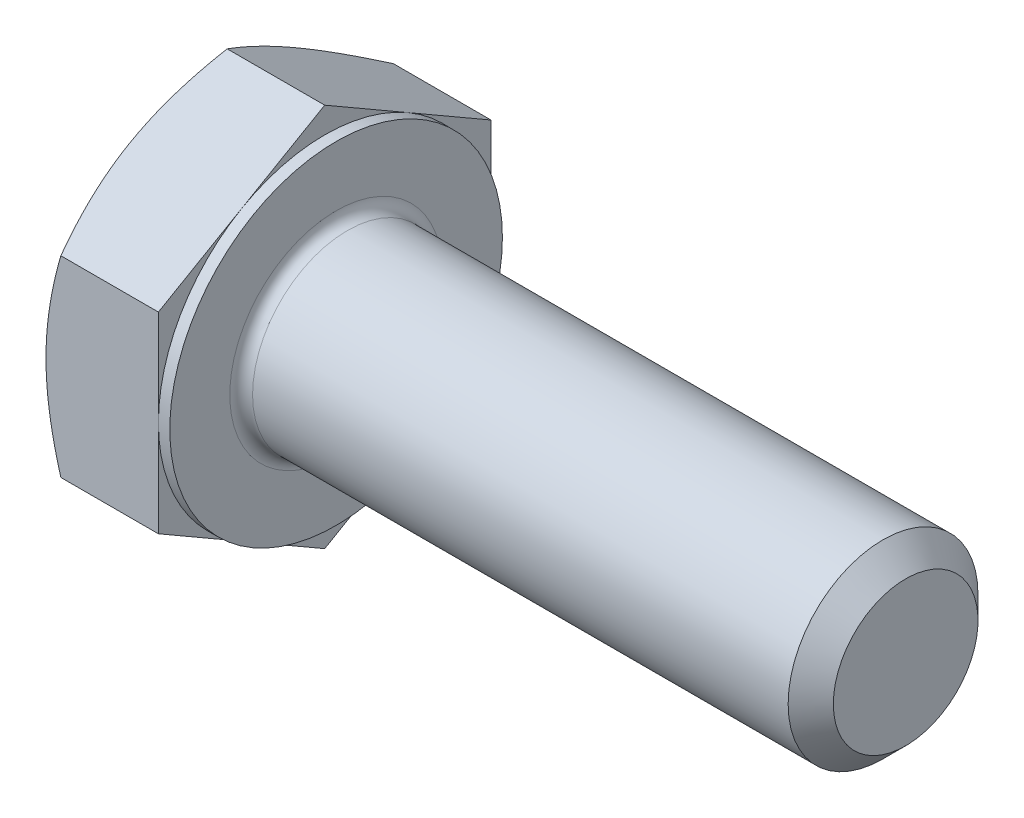
SolidWorks part; units mm, degrees
extrude "BaseHead" add sketch "Sketch1" along normal blind 4.1402
sketch "Sketch1" plane through (0, 0, 0) normal (1, 0, 0) x (0, 0, -1)
  line L0 (5.5626, 3.2116) -> (5.5626, -3.2116)
  line L1 (-5.5626, 3.2116) -> (-5.5626, -3.2116)
  line L2 (5.5626, -3.2116) -> (0, -6.4231)
  line L3 (0, -6.4231) -> (-5.5626, -3.2116)
  line L4 (5.5626, 3.2116) -> (0, 6.4231)
  line L5 (0, 6.4231) -> (-5.5626, 3.2116)
  dimension "Width_flats" = 11.1252
  dimension "D2" = 120
  dimension "D3" = 5.5626
  dimension "D4" = 5.5626
  dimension "D5" = 5.5626
revolve "HeadChamfer" cut sketch "Sketch3" angle 360 about L6
sketch "Sketch3" plane through (0, 0, 0) normal (0, 0, 1) x (1, 0, 0)
  line L0 (0, 5.5626) -> (4.163, 12.7731)
  line L1 (0, 6.4231) -> (0, 3.2116) construction
  line L2 (4.163, 12.7731) -> (4.163, 19.1231)
  line L3 (4.163, 19.1231) -> (-12.7, 19.1231)
  line L4 (-12.7, 19.1231) -> (-12.7, 5.5626)
  line L5 (-12.7, 5.5626) -> (0, 5.5626)
  line L6 (0, 0) -> (99.06, 0) construction
  line L7 (4.1402, 6.4231) -> (0, 6.4231) construction
  dimension "D1" = 5.5626
  dimension "D2" = 6.35
  dimension "D3" = 12.7
  dimension "D4" = 6.35
  dimension "Head_ch_ang" = 30
ref_plane "Plane1" through (0, 0, 0) normal (0, 0, 1) x (1, 0, 0)
ref_plane "Plane2" through (0, 0, 0) normal (0, 1, 0) x (1, 0, 0)
ref_plane "Plane3" through (0, 0, 0) normal (1, 0, 0) x (0, 0, -1)
sketch "BodySke" plane through (0, 0, 0) normal (0, 0, 1) x (1, 0, 0)
  line L0 (0, 3.2116) -> (0, -3.2116) construction
  line L1 (0, 0) -> (23.1902, 0)
  line L2 (0, 0) -> (0, 3.175)
  line L3 (0, 3.175) -> (22.4345, 3.175)
  line L4 (23.1902, 0) -> (23.1902, 2.4193)
  line L5 (4.1402, 6.4231) -> (4.1402, 3.2116) construction
  line L6 (23.1902, 2.4193) -> (22.4345, 3.175)
  line L7 (0, 0) -> (96.52, 0) construction
  line L8 (23.1902, -2.4193) -> (22.4345, -3.175) construction
  line L9 (0, -3.175) -> (22.4345, -3.175) construction
  line L10 (5.4102, 15.24) -> (5.4102, -1.27) construction
  line L11 (4.1402, 15.24) -> (4.1402, -1.27) construction
  line L12 (4.1402, 3.2116) -> (4.1402, -3.2116) construction
  dimension "Diameter" = 6.35
revolve "BaseBody" add sketch "BodySke" angle 360 about L7
cosmetic thread "ThreadCosmetic" [suppressed] parameters "Thread_length"=17.78, "Thread_minor"=4.8387
sketch "Sketch4" plane through (0, 0, 0) normal (0, 0, 1) x (1, 0, 0)
  line L1 (4.1402, 6.4231) -> (4.1402, 3.2116) construction
  line L2 (4.1402, 5.5626) -> (3.7592, 5.5626)
  line L3 (4.1402, 5.5626) -> (4.1402, 31.8231)
  line L4 (4.1402, 31.8231) -> (3.7592, 31.8231)
  line L5 (0, 0) -> (95.25, 0) construction
  line L6 (0, 0) -> (96.52, 0) construction
  line L7 (3.7592, 5.5626) -> (3.7592, 31.8231)
  line L8 (4.1402, 6.4231) -> (0.4968, 6.4231) construction
  dimension "D1" = 5.5626
  dimension "D2" = 25.4
revolve "BearingFace" cut sketch "Sketch4" angle 360 about L5
fillet "HeadFillet" radius 0.381 1 edges at (4.1402, 0, -3.175)
sketch "ThdSchSke" plane through (0, 0, 0) normal (0, 0, 1) x (1, 0, 0)
  line L0 (5.4102, -2.4193) -> (4.8811, -3.175)
  line L1 (5.4102, -2.4193) -> (5.9393, -3.175)
  line L2 (5.9393, -3.175) -> (5.9393, -3.9688)
  line L3 (-3.175, 0) -> (5.1513, 0) construction
  line L5 (5.9393, -3.9688) -> (4.8811, -3.9688)
  line L6 (4.8811, -3.9688) -> (4.8811, -3.175)
  dimension "Thread_minor" = 4.8387
  dimension "Diameter" = 6.35
  dimension "Start" = 5.4102
revolve "ThreadSchematic" [suppressed] cut sketch "ThdSchSke" angle 360 about L3
pattern_linear "ThdSchPat" [suppressed]
equation "\"D3@Sketch1\" = \"Width_flats@Sketch1\" / 2"
equation "\"D4@Sketch1\" = \"D3@Sketch1\""
equation "\"D5@Sketch1\" = \"D4@Sketch1\""
equation "\"Thread_minor@ThreadCosmetic\" = \"Minor_dia@BodySke\""
equation "\"D1@Sketch3\" = \"Width_flats@Sketch1\" / 2"
equation "\"D1@Sketch4\" = \"Width_flats@Sketch1\" / 2"
equation "\"Thread_length@ThreadCosmetic\" = ((sgn( (\"Length@BodySke\" - \"Advance@BodySke\" ) - \"Thread_nom@BodySke\" )-1)*( (\"Length@BodySke\" - \"Advance@BodySke\" ) - \"Thread_nom@BodySke\" ))/-2+ \"Thread_nom@BodySke\""
equation "\"Thread_minor@ThdSchSke\" = \"Minor_dia@BodySke\""
equation "\"Diameter@ThdSchSke\" = \"Diameter@BodySke\""
equation "\"Overcut@ThdSchSke\" = \"Diameter@BodySke\" * 1.25"
equation "\"Start@ThdSchSke\" = \"Head_ht@BaseHead\" + \"Length@BodySke\" - \"Thread_length@ThreadCosmetic\"  '---Non-countersunk---"
equation "\"Num_threads@ThdSchPat\" = int( \"Thread_length@ThreadCosmetic\" / \"Advance@BodySke\" + 0.999 )  + 1"
equation "\"Advance@ThdSchPat\" = \"Thread_length@ThreadCosmetic\" /  (\"Num_threads@ThdSchPat\" - 1) 'relax it"
equation "\"Num_threads@ThdSchPat\" = \"Num_threads@ThdSchPat\" - sgn( \"Num_threads@ThdSchPat\" - 1) '---chamfered tips only---"
